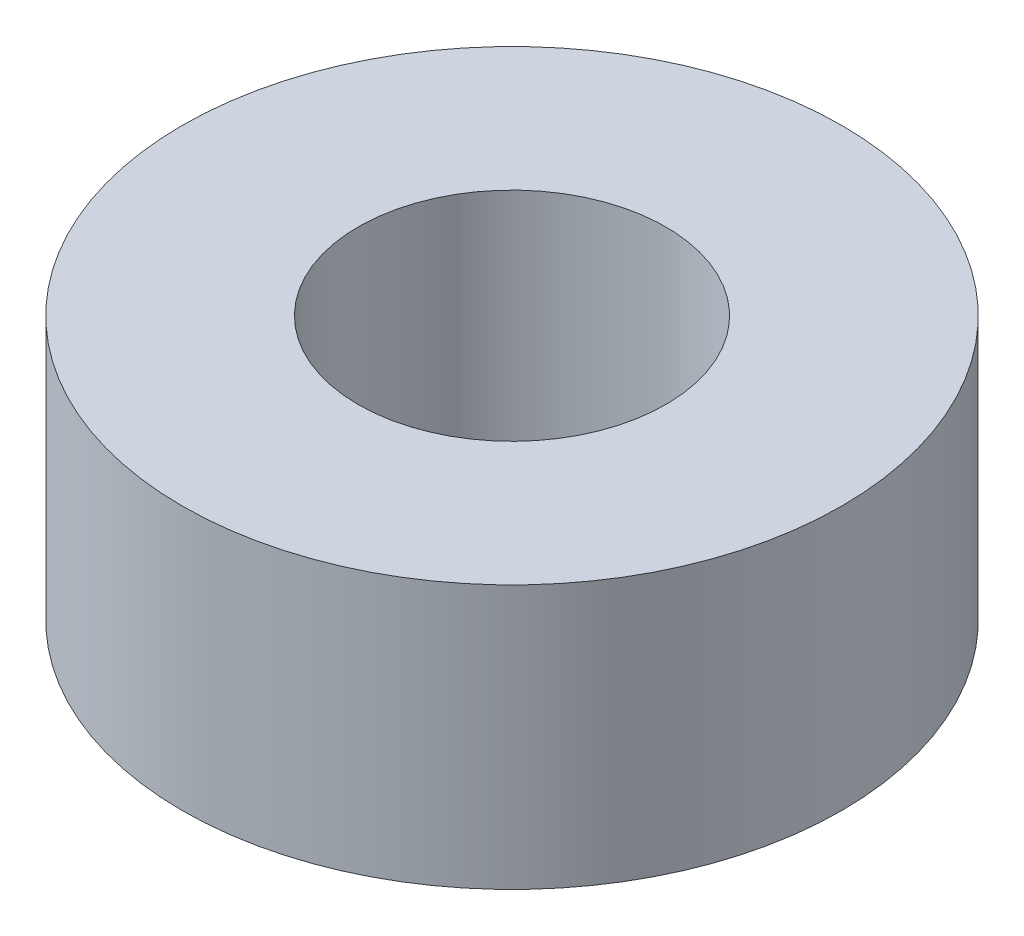
SolidWorks part; units mm, degrees
ref_plane "Front Plane" through (0, 0, 0) normal (0, 0, 1) x (1, 0, 0)
ref_plane "Top Plane" through (0, 0, 0) normal (0, 1, 0) x (1, 0, 0)
ref_plane "Right Plane" through (0, 0, 0) normal (1, 0, 0) x (0, 0, -1)
sketch "Sketch1" plane through (0, 0, 0) normal (0, 1, 0) x (1, 0, 0)
  circle A0 centre (0, 0) radius 1.75
  circle A1 centre (0, 0) radius 3.75
  dimension "D1" = 3.5
  dimension "D2" = 2
extrude "Boss-Extrude1" add sketch "Sketch1" along normal blind 3
